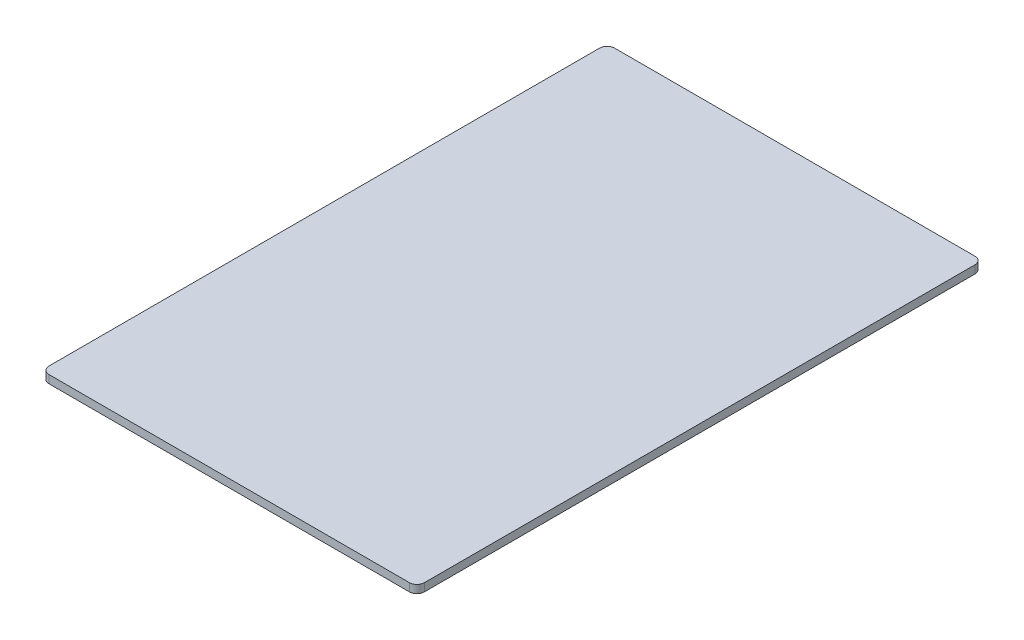
SolidWorks part; units mm, degrees
ref_plane "前视基准面" through (0, 0, 0) normal (0, 0, 1) x (1, 0, 0)
ref_plane "上视基准面" through (0, 0, 0) normal (0, 1, 0) x (1, 0, 0)
ref_plane "右视基准面" through (0, 0, 0) normal (1, 0, 0) x (0, 0, -1)
other "Configuration Table"
sketch "草图1" plane through (0, 0, 0) normal (0, 1, 0) x (1, 0, 0)
  line L0 (25.2806, 0) -> (100.2806, 0)
  line L1 (100.2806, 0) -> (100.2806, -113)
  line L2 (100.2806, -113) -> (25.2806, -113)
  line L3 (25.2806, -113) -> (25.2806, 0)
extrude "凸台-拉伸1" add sketch "草图1" along normal blind 1.6
fillet "圆角1" radius 1.5 4 edges at (100.2806, 0.8, 0) (100.2806, 0.8, 113) (25.2806, 0.8, 0) (25.2806, 0.8, 113)
